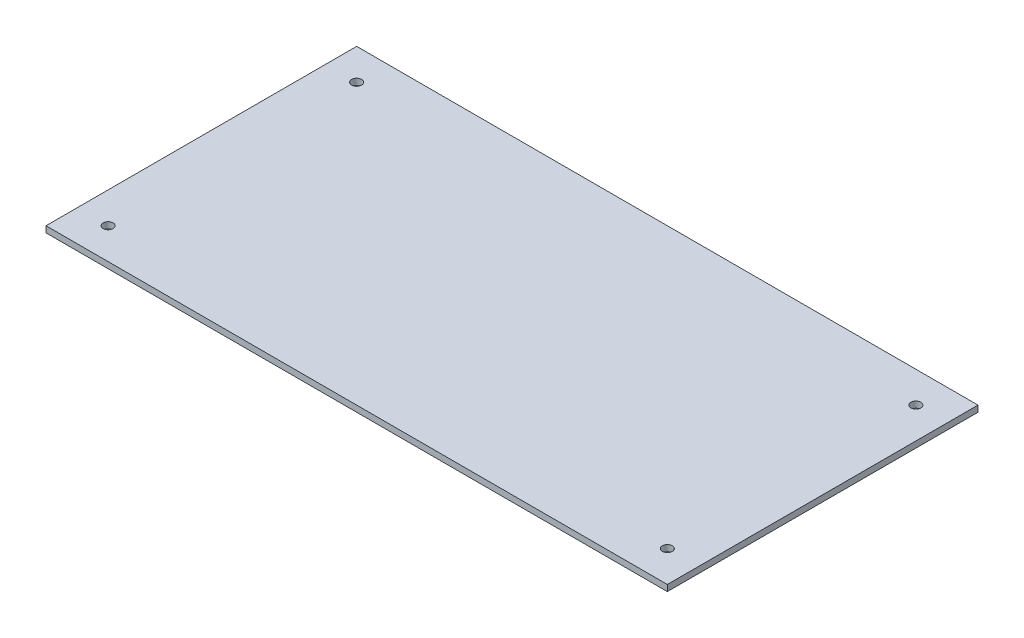
SolidWorks part; units mm, degrees
ref_plane "前视基准面" through (0, 0, 0) normal (0, 0, 1) x (1, 0, 0)
ref_plane "上视基准面" through (0, 0, 0) normal (0, 1, 0) x (1, 0, 0)
ref_plane "右视基准面" through (0, 0, 0) normal (1, 0, 0) x (0, 0, -1)
sketch "草图1" plane through (0, 0, 0) normal (0, 1, 0) x (1, 0, 0)
  line L1 (-100, -50) -> (100, -50)
  line L2 (-100, -50) -> (-100, 50)
  line L3 (-100, 50) -> (100, 50)
  line L4 (100, -50) -> (100, 50)
  line L5 (-100, -50) -> (100, 50) construction
  line L6 (-100, 50) -> (100, -50) construction
  point P0 (0, 0)
  dimension "D1" = 200
  dimension "D2" = 100
extrude "凸台-拉伸1" add sketch "草图1" along normal blind 2
sketch "草图2" plane through (0, 2, 0) normal (0, 1, 0) x (1, 0, 0)
  line L0 (0, 34.6126) -> (0, -62.6144) construction
  line L1 (-94.6724, 0) -> (91.3151, 0) construction
  circle A0 centre (-90, 40) radius 1.6
  circle A1 centre (90, 40) radius 1.6
  circle A2 centre (90, -40) radius 1.6
  circle A3 centre (-90, -40) radius 1.6
  dimension "D1" = 3.2
  dimension "D2" = 180
  dimension "D3" = 80
extrude "切除-拉伸1" cut sketch "草图2" against normal through all
